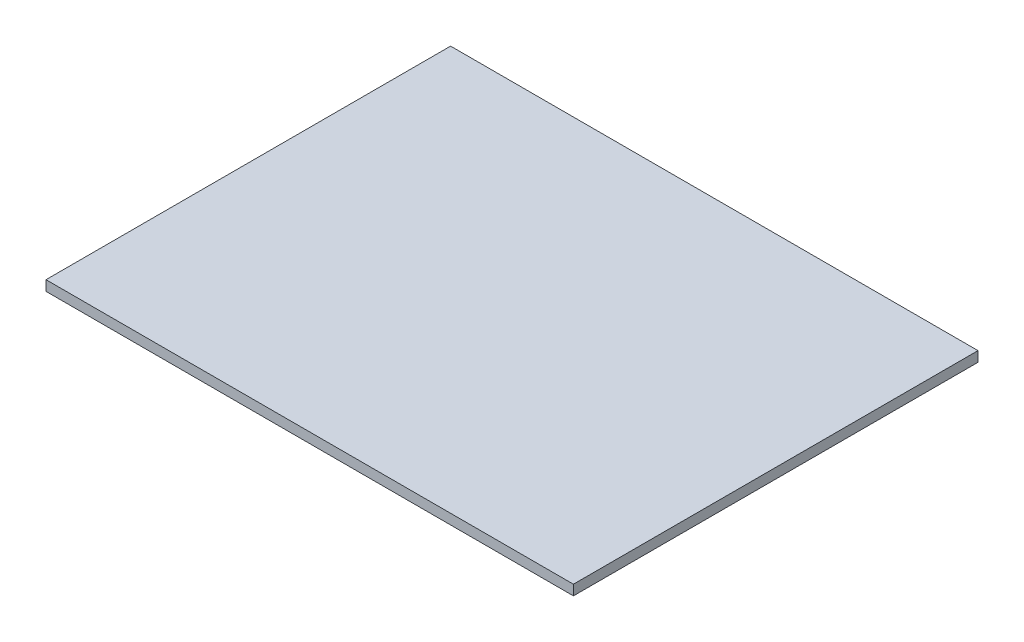
SolidWorks part; units mm, degrees
ref_plane "前视基准面" through (0, 0, 0) normal (0, 0, 1) x (1, 0, 0)
ref_plane "上视基准面" through (0, 0, 0) normal (0, 1, 0) x (1, 0, 0)
ref_plane "右视基准面" through (0, 0, 0) normal (1, 0, 0) x (0, 0, -1)
sketch "草图1" plane through (0, 0, 0) normal (0, 1, 0) x (1, 0, 0)
  line L1 (-799.1281, 494.7793) -> (136.8719, 494.7793)
  line L2 (-799.1281, 494.7793) -> (-799.1281, -223.2207)
  line L3 (-799.1281, -223.2207) -> (136.8719, -223.2207)
  line L4 (136.8719, 494.7793) -> (136.8719, -223.2207)
  dimension "D1" = 936
  dimension "D2" = 718
extrude "凸台-拉伸1" add sketch "草图1" along normal blind 18
